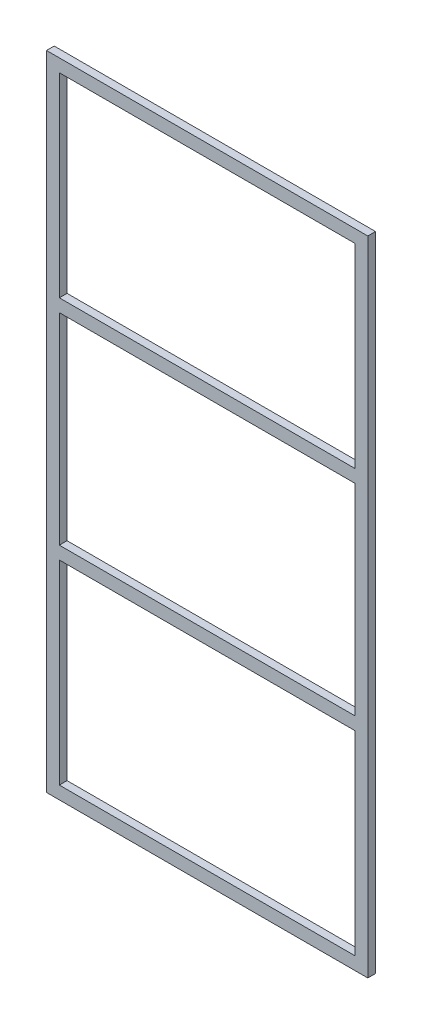
SolidWorks part; units mm, degrees
ref_plane "Plano frontal" through (0, 0, 0) normal (0, 0, 1) x (1, 0, 0)
ref_plane "Plano superior" through (0, 0, 0) normal (0, 1, 0) x (1, 0, 0)
ref_plane "Plano direito" through (0, 0, 0) normal (1, 0, 0) x (0, 0, -1)
sketch "Esboço1" plane through (0, 0, 0) normal (0, 0, 1) x (1, 0, 0)
  line L1 (0, 0) -> (250, 0)
  line L2 (0, 0) -> (0, -500)
  line L3 (0, -500) -> (250, -500)
  line L4 (250, 0) -> (250, -500)
extrude "Ressalto-extrusão1" add sketch "Esboço1" along normal blind 6
sketch "Esboço3" plane through (0, 0, 6) normal (0, 0, 1) x (1, 0, 0)
  line L0 (250, -500) -> (250, 0) construction
  line L2 (0, 0) -> (250, 0)
  line L3 (0, 0) -> (0, -166.6667)
  line L4 (0, -166.6667) -> (250, -166.6667)
  line L5 (250, 0) -> (250, -166.6667)
  line L6 (0, -166.6667) -> (250, -166.6667)
  line L7 (0, -166.6667) -> (0, -333.3367)
  line L8 (0, -333.3367) -> (250, -333.3367)
  line L9 (250, -166.6667) -> (250, -333.3367)
  line L10 (0, -333.3367) -> (250, -333.3367)
  line L11 (0, -333.3367) -> (0, -500)
  line L12 (0, -500) -> (250, -500)
  line L13 (250, -333.3367) -> (250, -500)
  line L14 (10, -10) -> (240, -10)
  line L15 (10, -10) -> (10, -161.6667)
  line L16 (10, -161.6667) -> (240, -161.6667)
  line L17 (240, -10) -> (240, -161.6667)
  line L18 (10, -171.6667) -> (240, -171.6667)
  line L19 (10, -171.6667) -> (10, -328.3367)
  line L20 (10, -328.3367) -> (240, -328.3367)
  line L21 (240, -171.6667) -> (240, -328.3367)
  line L22 (10, -338.3367) -> (240, -338.3367)
  line L23 (10, -338.3367) -> (10, -490)
  line L24 (10, -490) -> (240, -490)
  line L25 (240, -338.3367) -> (240, -490)
  dimension "D1" = 166.6667
  dimension "D2" = 166.67
  dimension "D3" = 10
  dimension "D4" = 5
  dimension "D5" = 10
  dimension "D6" = 10
  dimension "D7" = 5
  dimension "D8" = 5
  dimension "D9" = 10
  dimension "D10" = 10
  dimension "D11" = 10
  dimension "D12" = 5
extrude "Corte-extrusão1" cut sketch "Esboço3" against normal blind 10 contours L21 L18 L19 L20 | L17 L14 L15 L16 | L25 L22 L23 L24
